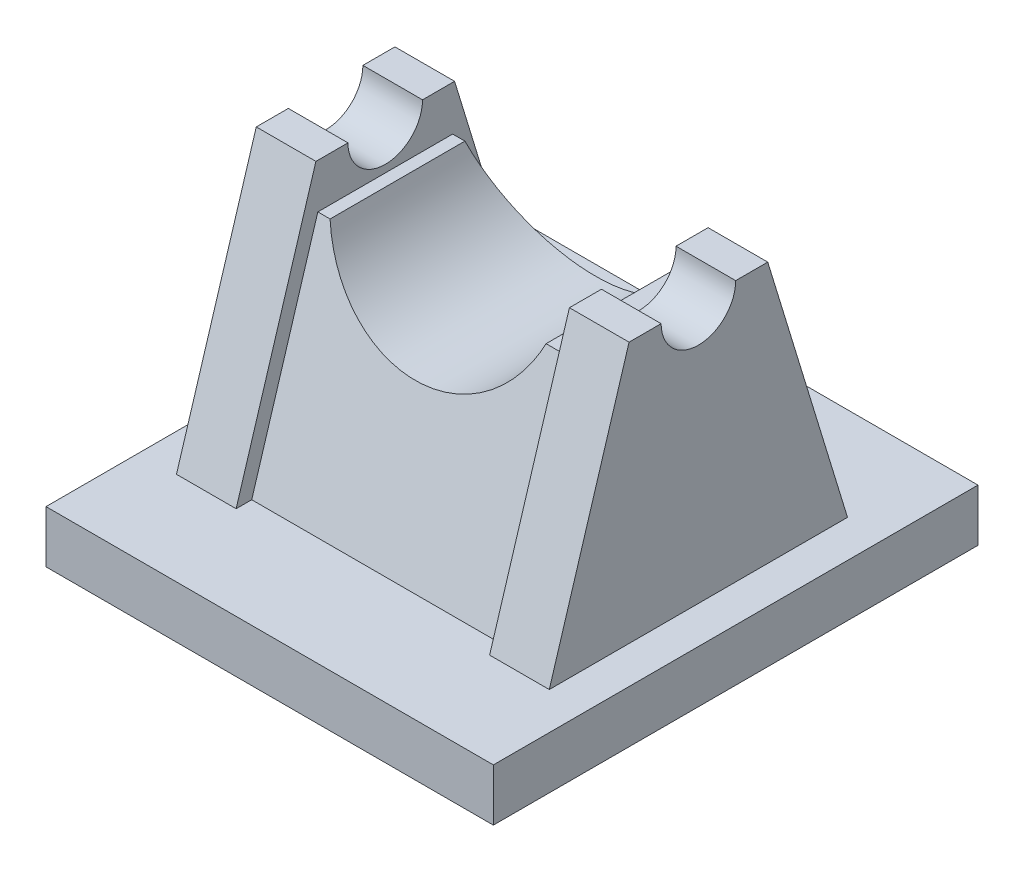
SolidWorks part; units mm, degrees
ref_plane "Front Plane" through (0, 0, 0) normal (0, 0, 1) x (1, 0, 0)
ref_plane "Top Plane" through (0, 0, 0) normal (0, 1, 0) x (1, 0, 0)
ref_plane "Right Plane" through (0, 0, 0) normal (1, 0, 0) x (0, 0, -1)
sketch "Sketch2" plane through (0, 0, 0) normal (1, 0, 0) x (0, 0, -1)
  line L4 (40, 0) -> (0, 0)
  line L5 (20, 0) -> (20, 38.9671) construction
  line L6 (0, 0) -> (10.7006, 35)
  line L7 (10.7006, 35) -> (15, 35)
  line L8 (15, 35) -> (20, 35) construction
  line L9 (29.2994, 35) -> (25, 35)
  line L10 (40, 0) -> (29.2994, 35)
  arc A1 (15, 35) -> (25, 35) centre (20, 35) ccw
  dimension "D4" = 5
  dimension "D1" = 40
  dimension "D2" = 35
  dimension "D3" = 73
extrude "Boss-Extrude1" add sketch "Sketch2" against normal blind 50
sketch "Sketch3" plane through (0, 0, 0) normal (1, 0, 0) x (0, 0, -1)
  line L5 (10.7006, 35) -> (0, 0)
  line L6 (0, 0) -> (40, 0)
  line L7 (40, 0) -> (29.2994, 35)
  line L8 (29.2994, 35) -> (25, 35)
  line L9 (15, 35) -> (10.7006, 35)
  line L10 (10.7006, 35) -> (0, 0)
  line L11 (0, 0) -> (2.0914, 0)
  line L12 (40, 0) -> (29.2994, 35)
  line L13 (29.2994, 35) -> (27.7309, 35)
  line L14 (12.2691, 35) -> (10.7006, 35)
  line L20 (10.9576, 29) -> (2.0914, 0)
  line L21 (20, 35) -> (20, 0) construction
  line L22 (29.0424, 29) -> (37.9086, 0)
  line L23 (37.9086, 0) -> (40, 0)
  line L24 (12.2691, 35) -> (27.7309, 35)
  line L25 (10.9576, 29) -> (29.0424, 29)
  arc A1 (15, 35) -> (25, 35) centre (20, 35) ccw
  dimension "D2" = 2
  dimension "D3" = 6
  dimension "D1" = 0
extrude "Cut-Extrude1" cut sketch "Sketch3" against normal blind 34 from offset 8 contours L10 L11 L20 L25 L22 L23 L12 L13 L24 L14 offset against normal yes
sketch "Sketch4" plane through (0, 0, 0) normal (0, 0, 1) x (1, 0, 0)
  line L5 (-8, 29) -> (-42, 29) construction
  line L17 (-11.389, 29) -> (-40.3602, 29)
  line L24 (-42.8746, 34.5152) -> (-8.8746, 34.5152) construction
  arc A0 (-40.3602, 29) -> (-11.389, 29) centre (-25.8746, 34.5152) ccw
  dimension "D1" = 31
extrude "Cut-Extrude2" cut sketch "Sketch4" against normal blind 34
sketch "Sketch5" plane through (0, 0, 0) normal (0, -1, 0) x (1, 0, 0)
  line L0 (0, -20) -> (-50, -20) construction
  line L1 (0, 0) -> (0, -40) construction
  line L2 (-50, 0) -> (-50, -40) construction
  line L7 (-25, -2.0914) -> (-25, -37.9086) construction
  line L8 (-42, -2.0914) -> (-8, -2.0914) construction
  line L9 (-42, -37.9086) -> (-8, -37.9086) construction
  line L11 (-55, -52.5) -> (5, -52.5)
  line L12 (-55, -52.5) -> (-55, 12.5)
  line L13 (-55, 12.5) -> (5, 12.5)
  line L14 (5, -52.5) -> (5, 12.5)
  line L15 (-55, -52.5) -> (5, 12.5) construction
  line L16 (-55, 12.5) -> (5, -52.5) construction
  point P12 (-25, -20)
  dimension "D2" = 65
  dimension "D1" = 60
extrude "Boss-Extrude3" add sketch "Sketch5" along normal blind 7
